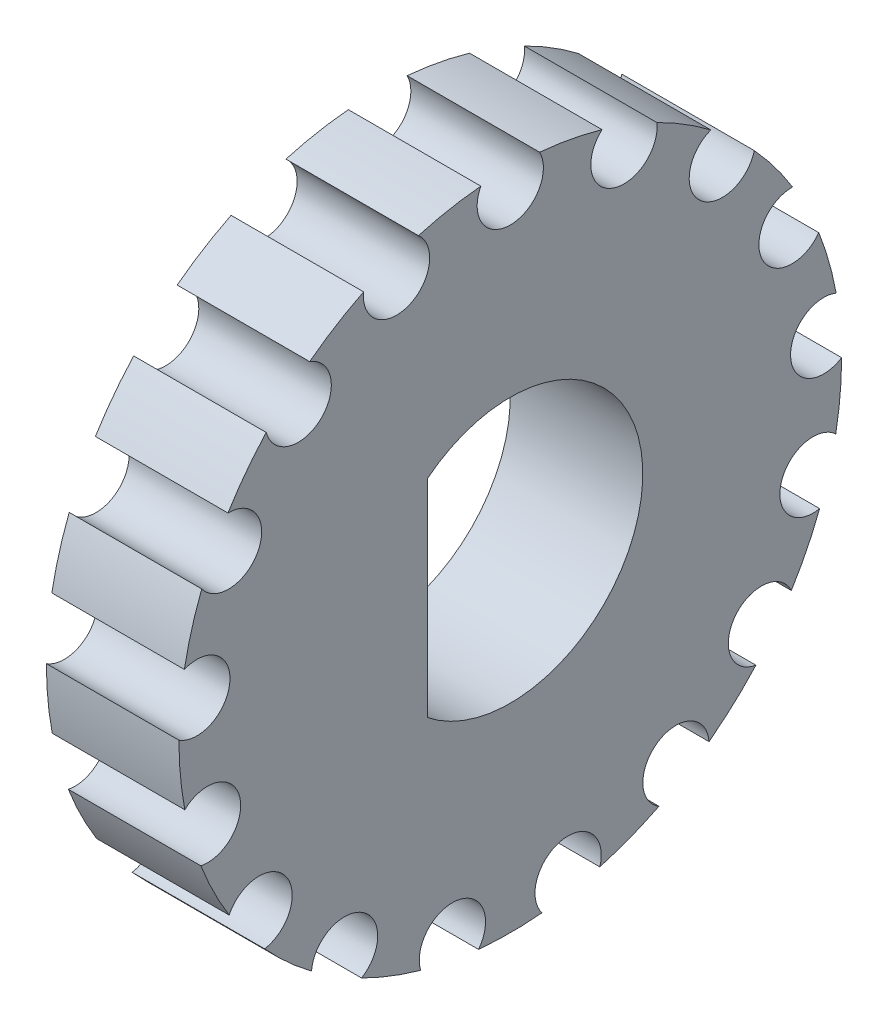
SolidWorks part; units mm, degrees
ref_plane "Спереди" through (0, 0, 0) normal (0, 0, 1) x (1, 0, 0)
ref_plane "Сверху" through (0, 0, 0) normal (0, 1, 0) x (1, 0, 0)
ref_plane "Справа" through (0, 0, 0) normal (1, 0, 0) x (0, 0, -1)
sketch "Эскиз1" plane through (0, 0, 0) normal (1, 0, 0) x (0, 0, -1)
  line L0 (0, 0) -> (0, 15.7337) construction
  line L1 (0, 0) -> (0, -13.5971) construction
  circle A0 centre (0, 0) radius 10
  circle A1 centre (0, 0) radius 9
  dimension "D1" = 20
  dimension "D2" = 1
extrude "Бобышка-Вытянуть2" add sketch "Эскиз1" along normal blind 4 contours A0
sketch "Эскиз2" plane through (0, 0, 0) normal (-1, 0, 0) x (0, 0, 1)
  line L0 (0, 0) -> (0, 10.8986) construction
  line L1 (0, 0) -> (0, 9.5) construction
  circle A2 centre (0, 9.5) radius 1
  circle A3 centre (3.4318, 8.8585) radius 1
  circle A4 centre (6.4001, 7.0206) radius 1
  circle A5 centre (8.5041, 4.2345) radius 1
  circle A6 centre (9.4595, 0.8765) radius 1
  circle A7 centre (9.1373, -2.5998) radius 1
  circle A8 centre (7.5812, -5.725) radius 1
  circle A9 centre (5.0011, -8.0771) radius 1
  circle A10 centre (1.7456, -9.3382) radius 1
  circle A11 centre (-1.7456, -9.3382) radius 1
  circle A12 centre (-5.0011, -8.0771) radius 1
  circle A13 centre (-7.5812, -5.725) radius 1
  circle A14 centre (-9.1373, -2.5998) radius 1
  circle A15 centre (-9.4595, 0.8765) radius 1
  circle A16 centre (-8.5041, 4.2345) radius 1
  circle A17 centre (-6.4001, 7.0206) radius 1
  circle A18 centre (-3.4318, 8.8585) radius 1
  dimension "D2" = 2
  dimension "D3" = 17
  dimension "D4" = 9.5
extrude "Вырез-Вытянуть1" cut sketch "Эскиз2" against normal blind 4
sketch "Эскиз3" plane through (4, 0, 0) normal (1, 0, 0) x (0, 0, -1)
  line L0 (-2.5, 3.1225) -> (-2.5, -3.1225)
  arc A0 (-2.5, -3.1225) -> (-2.5, 3.1225) centre (0, 0) ccw
  dimension "D1" = 8
  dimension "D2" = 2.5
extrude "Вырез-Вытянуть2" cut sketch "Эскиз3" against normal blind 4
